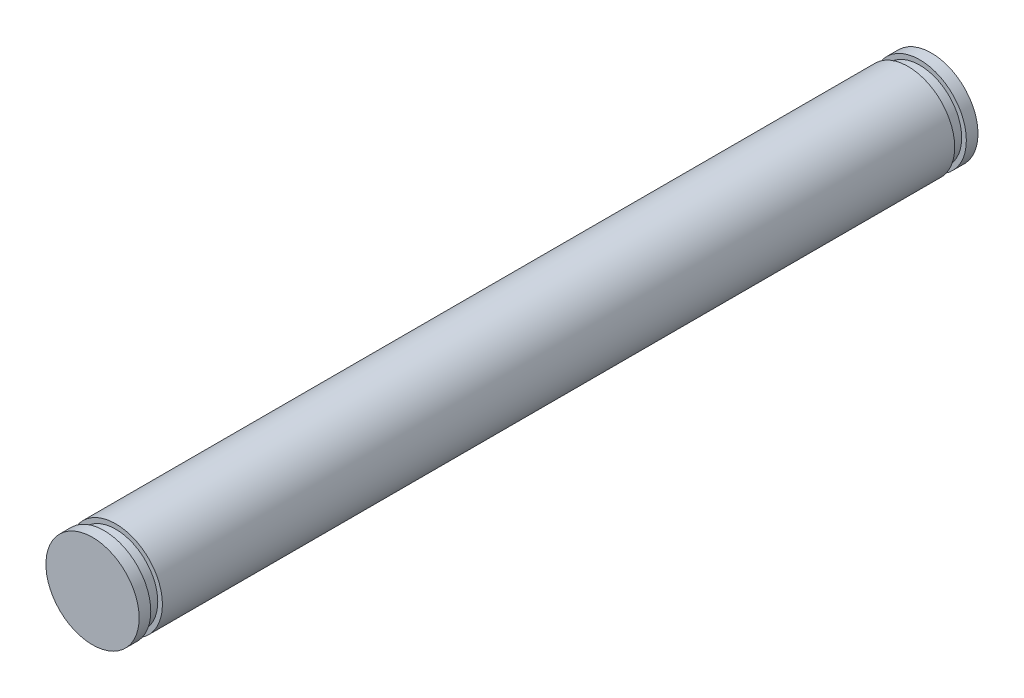
SolidWorks part; units mm, degrees
material "合金钢"
ref_plane "前视基准面" through (0, 0, 0) normal (0, 0, 1) x (1, 0, 0)
ref_plane "上视基准面" through (0, 0, 0) normal (0, 1, 0) x (1, 0, 0)
ref_plane "右视基准面" through (0, 0, 0) normal (1, 0, 0) x (0, 0, -1)
other "Configuration Table"
sketch "草图1" plane through (0, 0, 0) normal (0, 0, 1) x (1, 0, 0)
  circle A0 centre (0, 0) radius 4
  dimension "D1" = 8
extrude "凸台-拉伸1" add sketch "草图1" along normal mid plane 72
ref_plane "基准面1" through (0, 0, 34) normal (0, 0, 1) x (1, 0, 0)
sketch "草图2" plane through (0, 0, 34) normal (0, 0, 1) x (1, 0, 0)
  circle A0 centre (0, 0) radius 4
  circle A1 centre (0, 0) radius 3.6
  dimension "D1" = 8
  dimension "D2" = 7.2
extrude "切除-拉伸1" cut sketch "草图2" along normal blind 1
mirror "镜向1" about plane through (0, 0, 0) normal (0, 0, 1) of "切除-拉伸1"
